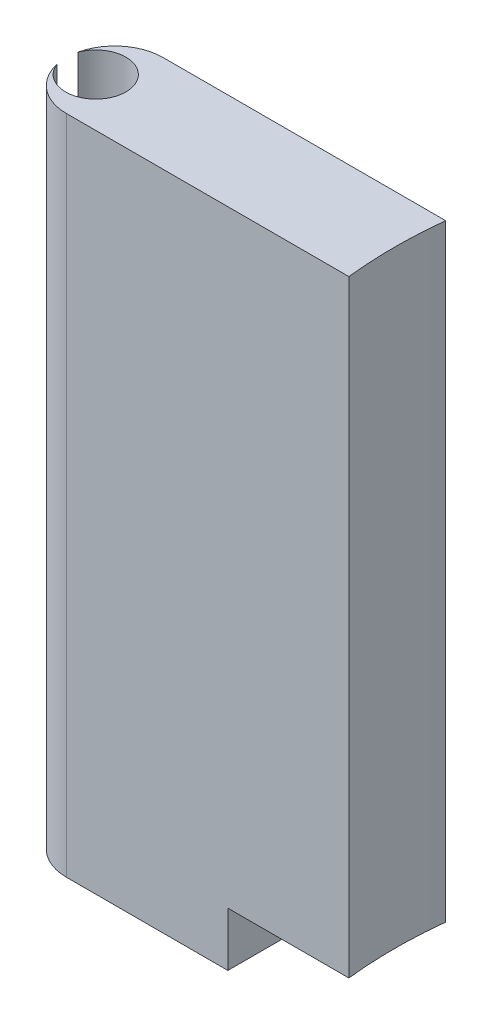
SolidWorks part; units mm, degrees
ref_plane "Front Plane" through (0, 0, 0) normal (0, 0, 1) x (1, 0, 0)
ref_plane "Top Plane" through (0, 0, 0) normal (0, 1, 0) x (1, 0, 0)
ref_plane "Right Plane" through (0, 0, 0) normal (1, 0, 0) x (0, 0, -1)
sketch "Sketch1" plane through (0, 0, 0) normal (0, 1, 0) x (1, 0, 0)
  line L4 (-113.5952, 7.62) -> (-69.1112, 7.62)
  line L5 (-113.5952, -7.62) -> (-69.1112, -7.62)
  arc A0 (-69.1112, 7.62) -> (-69.1112, -7.62) centre (0, 0) ccw
  arc A1 (-113.5952, 7.62) -> (-113.5952, -7.62) centre (-113.5952, 0) ccw
  point P5 (-69.53, 0)
  dimension "D1" = 139.06
  dimension "D2" = 44.484
extrude "Boss-Extrude1" add sketch "Sketch1" along normal blind 104.14
sketch "Sketch3" plane through (0, 104.14, 0) normal (0, 1, 0) x (1, 0, 0)
  line L0 (-121.1509, 0) -> (-121.2152, 0) construction
  circle A0 centre (-116.5789, 0) radius 4.75
  arc A1 (-113.5952, 7.62) -> (-113.5952, -7.62) centre (-113.5952, 0) ccw construction
  point P4 (-121.2152, 0)
  point P9 (-120.7585, 0)
  point P10 (-121.1509, 0)
  dimension "D1" = 4.572
extrude "Cut-Extrude4" cut sketch "Sketch3" against normal up to surface (104.14 mm away) contours A0 up to face at (-93.3629, 0, 0)
sketch "Sketch4" plane through (0, 0, 0) normal (0, -1, 0) x (1, 0, 0)
  line L0 (-69.1112, -7.62) -> (-113.5952, -7.62) construction
  line L1 (-69.1112, 7.62) -> (-88.1612, 7.62)
  line L2 (-69.1112, 7.62) -> (-69.1112, -7.62)
  line L3 (-69.1112, -7.62) -> (-88.1612, -7.62)
  line L4 (-88.1612, 7.62) -> (-88.1612, -7.62)
  dimension "D1" = 19.05
extrude "Cut-Extrude5" cut sketch "Sketch4" against normal blind 8.5
sketch "Sketch5" plane through (0, 8.5, 0) normal (0, -1, 0) x (1, 0, 0)
  line L0 (-69.1112, 7.62) -> (-69.1112, -7.62) construction
  line L1 (-69.1112, 0) -> (-89.1581, 0) construction
  arc A0 (-69.1112, 7.62) -> (-69.1112, -7.62) centre (0, 0) ccw construction
  circle A1 centre (-77.3231, 0) radius 3
  point P9 (-69.53, 0)
  point P12 (-66.3231, 0)
  dimension "D1" = 11
extrude "Cut-Extrude6" cut sketch "Sketch5" against normal blind 19.05 contours A1
